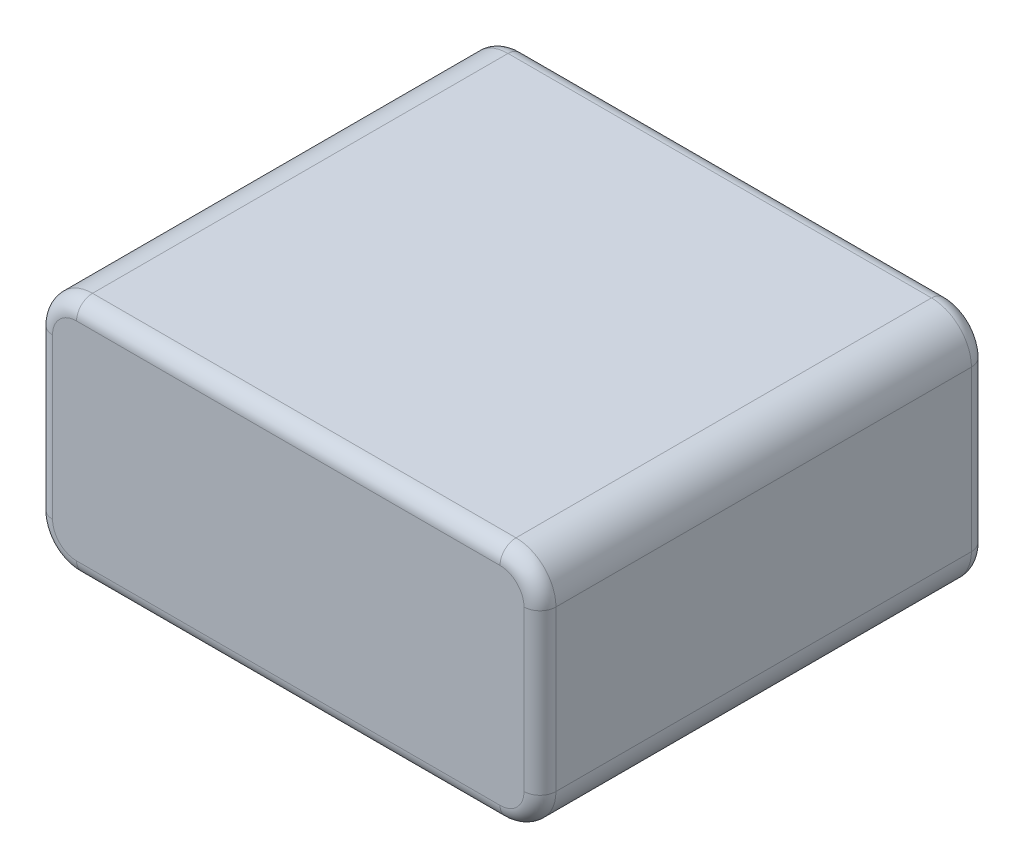
SolidWorks part; units mm, degrees
ref_plane "Front Plane" through (0, 0, 0) normal (0, 0, 1) x (1, 0, 0)
ref_plane "Top Plane" through (0, 0, 0) normal (0, 1, 0) x (1, 0, 0)
ref_plane "Right Plane" through (0, 0, 0) normal (1, 0, 0) x (0, 0, -1)
sketch "Sketch2" plane through (0, 0, 0) normal (0, 1, 0) x (1, 0, 0)
  line L1 (31.5, -28) -> (-31.5, -28)
  line L2 (31.5, -28) -> (31.5, 28)
  line L3 (31.5, 28) -> (-31.5, 28)
  line L4 (-31.5, -28) -> (-31.5, 28)
  line L5 (31.5, -28) -> (-31.5, 28) construction
  line L6 (31.5, 28) -> (-31.5, -28) construction
  point P0 (0, 0)
  dimension "D1" = 63
  dimension "D2" = 56
extrude "Boss-Extrude1" add sketch "Sketch2" along normal blind 30
fillet "Fillet1" radius 5 4 edges at (-31.5, 0, 0) (-31.5, 30, 0) (31.5, 0, 0) (31.5, 30, 0)
fillet "Fillet2" radius 2 16 edges at (30.0355, 1.4645, -28) (31.5, 15, -28) (30.0355, 28.5355, -28) (0, 30, -28) (-30.0355, 28.5355, -28) (-31.5, 15, -28) (-30.0355, 1.4645, -28) (0, 0, -28) (-30.0355, 28.5355, 28) (0, 30, 28) (30.0355, 28.5355, 28) (31.5, 15, 28) (30.0355, 1.4645, 28) (0, 0, 28) (-30.0355, 1.4645, 28) (-31.5, 15, 28)
